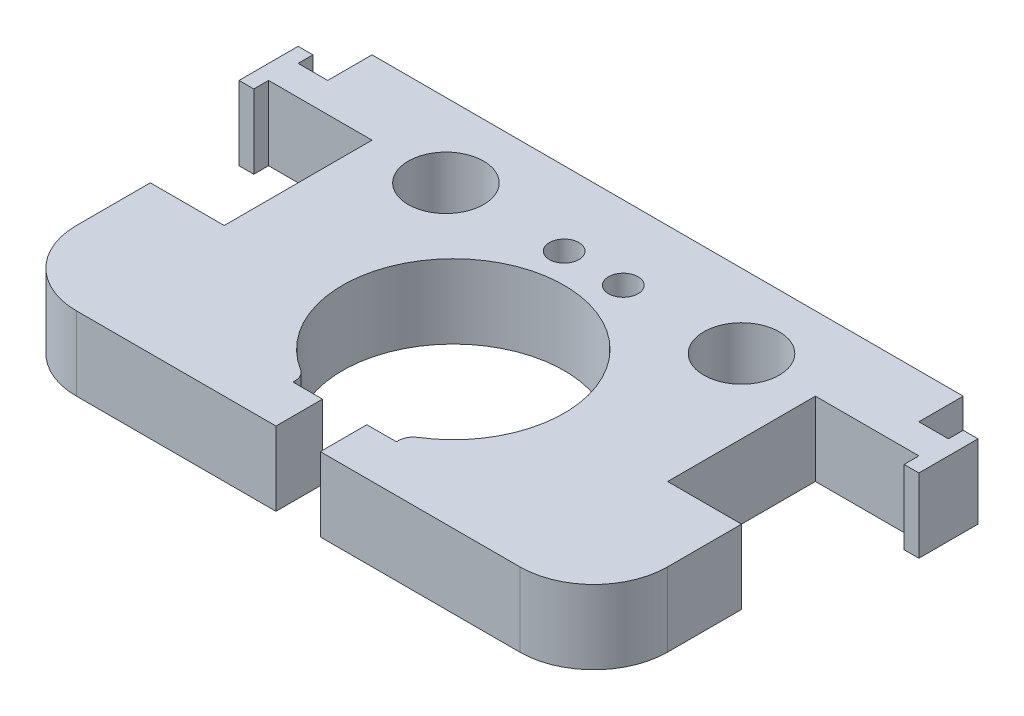
SolidWorks part; units mm, degrees
ref_plane "前视基准面" through (0, 0, 0) normal (0, 0, 1) x (1, 0, 0)
ref_plane "上视基准面" through (0, 0, 0) normal (0, 1, 0) x (1, 0, 0)
ref_plane "右视基准面" through (0, 0, 0) normal (1, 0, 0) x (0, 0, -1)
sketch "草图1" plane through (0, 0, 0) normal (0, 1, 0) x (1, 0, 0)
  line L0 (35, 20) -> (37, 20)
  line L1 (5, 0) -> (13.5, 0)
  line L2 (-5, 10) -> (-5, 5)
  line L3 (0, 25) -> (10, 25)
  line L4 (-5, 20) -> (0, 20)
  line L5 (5, 31.7923) -> (5, -5.1673) construction
  line L6 (25, 32.4364) -> (25, -5.1673) construction
  line L7 (15, 34.6911) -> (15, 0) construction
  line L8 (13.5, 3.1515) -> (11.5, 3.1515)
  line L9 (0, 25) -> (-5, 25)
  line L10 (-5, 25) -> (-5, 22)
  line L11 (0, 0) -> (5, 0)
  line L12 (37, 20) -> (37, 19)
  line L13 (16.5, 0) -> (25, 0)
  line L14 (20, 25) -> (30, 25)
  line L15 (13.5, 3.1515) -> (13.5, 0)
  line L16 (16.5, 3.1515) -> (18.5, 3.1515)
  line L17 (16.5, 3.1515) -> (16.5, 0)
  line L18 (18.5, 3.1515) -> (18.5, 3.2889)
  line L19 (11.5, 3.1515) -> (11.5, 3.2889)
  line L20 (10, 25) -> (20, 25)
  line L21 (1.4279, 20) -> (42.7109, 20) construction
  line L22 (25, 0) -> (30, 0)
  line L23 (35, 5) -> (35, 10)
  line L24 (35, 25) -> (30, 25)
  line L25 (37, 19) -> (38, 19)
  line L26 (-5, 10) -> (0, 10)
  line L27 (0, 20) -> (0, 10)
  line L28 (35, 20) -> (30, 20)
  line L29 (38, 19) -> (38, 23)
  line L30 (35, 10) -> (30, 10)
  line L31 (30, 20) -> (30, 10)
  line L32 (35, 22) -> (35, 25)
  line L33 (38, 23) -> (37, 23)
  line L34 (37, 23) -> (37, 22)
  line L35 (37, 22) -> (35, 22)
  line L36 (-5, 20) -> (-7, 20)
  line L37 (-7, 20) -> (-7, 19)
  line L38 (-7, 19) -> (-8, 19)
  line L39 (-8, 19) -> (-8, 23)
  line L40 (-8, 23) -> (-7, 23)
  line L41 (-7, 23) -> (-7, 22)
  line L42 (-7, 22) -> (-5, 22)
  circle A0 centre (5, 20) radius 2.55
  circle A1 centre (25, 20) radius 2.55
  arc A2 (18.9706, 4.1373) -> (11.0294, 4.1373) centre (15, 10.5) ccw
  arc A3 (18.5, 3.2889) -> (18.9706, 4.1373) centre (19.5, 3.2889) cw
  arc A4 (11.5, 3.2889) -> (11.0294, 4.1373) centre (10.5, 3.2889) ccw
  circle A5 centre (13, 20) radius 1
  circle A6 centre (17, 20) radius 1
  arc A7 (30, 0) -> (35, 5) centre (30, 5) ccw
  arc A8 (-5, 5) -> (0, 0) centre (0, 5) ccw
  point P40 (0, 0)
  point P53 (32.5, 20)
  dimension "D6" = 5.1
  dimension "D10" = 7.5
  dimension "D12" = 1
  dimension "D13" = 10
  dimension "D7" = 5
  dimension "D5" = 2
  dimension "D9" = 5.1
  dimension "D16" = 2
  dimension "D1" = 25
  dimension "D2" = 30
  dimension "D3" = 5
  dimension "D4" = 5
  dimension "D8" = 10
  dimension "D11" = 1.5
  dimension "D14" = 5
  dimension "D15" = 5
  dimension "D17" = 2
  dimension "D18" = 2
  dimension "D19" = 46
extrude "凸台-拉伸1" add sketch "草图1" along normal blind 5
